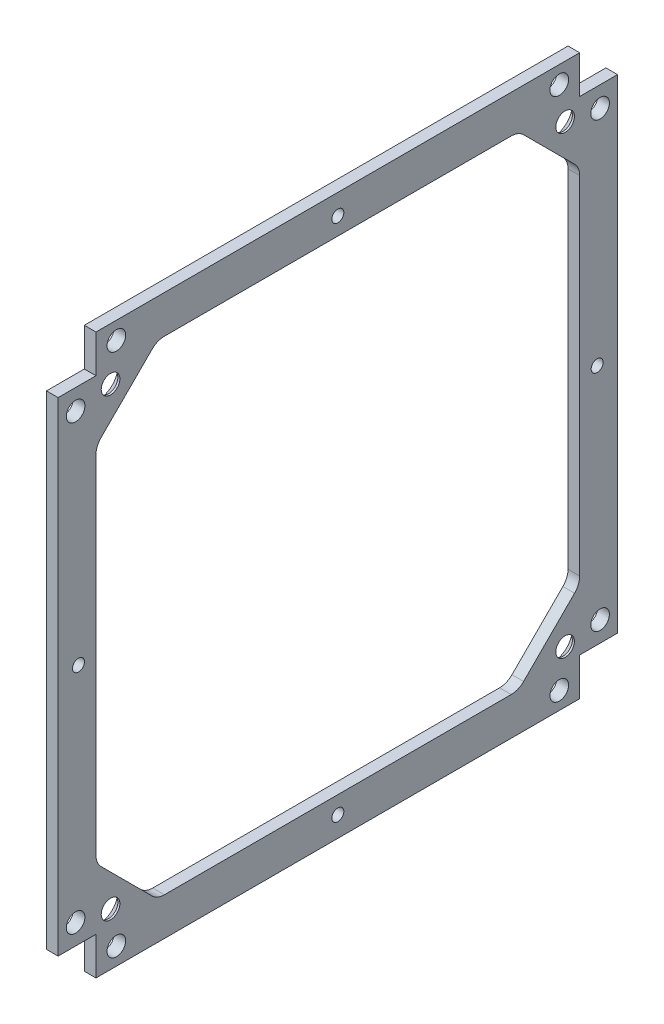
SolidWorks part; units mm, degrees
ref_plane "Front Plane" through (0, 0, 0) normal (0, 0, 1) x (1, 0, 0)
ref_plane "Top Plane" through (0, 0, 0) normal (0, 1, 0) x (1, 0, 0)
ref_plane "Right Plane" through (0, 0, 0) normal (1, 0, 0) x (0, 0, -1)
sketch "Sketch2" plane through (-51.4936, 0, 0) normal (-1, 0, 0) x (0, 0, 1)
  line L0 (0.9347, 3.4519) -> (7.4347, 3.4519)
  line L1 (7.4347, 3.4519) -> (7.4347, 86.4519)
  line L2 (0.9347, 92.9519) -> (-82.0653, 92.9519)
  line L3 (-88.5653, 86.4519) -> (-88.5653, 3.4519)
  line L4 (-82.0653, -3.0481) -> (0.9347, -3.0481)
  line L5 (0.9347, -3.0481) -> (0.9347, 3.4519)
  line L6 (-82.0653, -3.0481) -> (-82.0653, 3.4519)
  line L7 (-82.0653, 3.4519) -> (-88.5653, 3.4519)
  line L8 (-71.5653, 86.4519) -> (-82.0653, 75.9519)
  line L9 (-82.0653, 75.9519) -> (-82.0653, 13.9519)
  line L10 (-82.0653, 13.9519) -> (-71.5653, 3.4519)
  line L11 (-88.5653, 86.4519) -> (-82.0653, 86.4519)
  line L12 (-82.0653, 92.9519) -> (-82.0653, 86.4519)
  line L13 (-71.5653, 3.4519) -> (-9.5653, 3.4519)
  line L14 (-9.5653, 3.4519) -> (0.9347, 13.9519)
  line L15 (7.4347, 86.4519) -> (0.9347, 86.4519)
  line L16 (0.9347, 92.9519) -> (0.9347, 86.4519)
  line L17 (0.9347, 13.9519) -> (0.9347, 75.9519)
  line L18 (0.9347, 75.9519) -> (-9.5653, 86.4519)
  line L19 (-9.5653, 86.4519) -> (-71.5653, 86.4519)
  dimension "D1" = 6.5
  dimension "D2" = 6.5
  dimension "D3" = 6.5
  dimension "D4" = 6.5
  dimension "D5" = 6.5
  dimension "D6" = 6.5
extrude "Boss-Extrude2" add sketch "Sketch2" along normal blind 2
hole_wizard "CSK for M3 Flat Countersunk Head Screw3" positions "Sketch11" profile "Sketch10" countersink size "M3" standard "JIS" end condition through all
sketch "Sketch11" plane through (-53.4936, 0, 0) normal (-1, 0, 0) x (0, 0, 1)
  line L0 (0.9347, 3.4519) -> (7.4347, 3.4519) construction
  line L1 (0.9347, -3.0481) -> (0.9347, 3.4519) construction
  point P0 (-1.5653, 5.9519)
  dimension "D1" = 2.5
  dimension "D2" = 2.5
sketch "Sketch10" plane through (-53.4936, 5.9519, -1.5653) normal (0, 1, 0) x (0, 0, 1)
  line L0 (0, 0) -> (0, 2)
  line L1 (0, 2) -> (1.6, 2)
  line L2 (1.6, 2) -> (1.6, 1.65)
  line L3 (1.6, 1.65) -> (3.25, 0)
  line L5 (3.25, 0) -> (0, 0)
  line L6 (-1.6, 1.65) -> (-3.25, 0) construction
  line L11 (0, -6.35) -> (0, 107.95) construction
  dimension "Thru Hole Dia." = 3.2
  dimension "Thru Hole Depth" = 2
  dimension "Near C'Sink Dia." = 6.5
  dimension "Near C'Sink Angle" = 90
hole_wizard "Ø3.2 (3.2) Diameter Hole1" positions "Sketch13" profile "Sketch12" hole size "Ø3.2" standard "Ansi Metric" end condition up to next
sketch "Sketch13" plane through (-53.4936, 0, 0) normal (-1, 0, 0) x (0, 0, 1)
  line L0 (0.9347, 3.4519) -> (7.4347, 3.4519) construction
  line L1 (7.4347, 3.4519) -> (7.4347, 86.4519) construction
  point P0 (4.4347, 6.9519)
  dimension "D1" = 3.5
  dimension "D2" = 3
sketch "Sketch12" plane through (-53.4936, 6.9519, 4.4347) normal (0, 1, 0) x (0, 0, 1)
  line L0 (0, 0) -> (0, 2)
  line L1 (0, 2) -> (1.6, 2)
  line L2 (1.6, 2) -> (1.6, 0)
  line L5 (1.6, 0) -> (0, 0)
  line L11 (0, -6.35) -> (0, 107.95) construction
  dimension "Thru Hole Dia." = 3.2
  dimension "Thru Hole Depth" = 2
hole_wizard "Ø3.2 (3.2) Diameter Hole2" positions "Sketch15" profile "Sketch14" hole size "Ø3.2" standard "Ansi Metric" end condition up to next
sketch "Sketch15" plane through (-53.4936, 0, 0) normal (-1, 0, 0) x (0, 0, 1)
  line L0 (0.9347, -3.0481) -> (0.9347, 3.4519) construction
  line L1 (-82.0653, -3.0481) -> (0.9347, -3.0481) construction
  point P0 (-2.5653, -0.0481)
  dimension "D1" = 3.5
  dimension "D2" = 3
sketch "Sketch14" plane through (-53.4936, -0.0481, -2.5653) normal (0, 1, 0) x (0, 0, 1)
  line L0 (0, 0) -> (0, 2)
  line L1 (0, 2) -> (1.6, 2)
  line L2 (1.6, 2) -> (1.6, 0)
  line L5 (1.6, 0) -> (0, 0)
  line L11 (0, -6.35) -> (0, 107.95) construction
  dimension "Thru Hole Dia." = 3.2
  dimension "Thru Hole Depth" = 2
hole_wizard "Ø3.2 (3.2) Diameter Hole3" positions "Sketch19" profile "Sketch18" hole size "Ø3.2" standard "Ansi Metric" end condition up to next
sketch "Sketch19" plane through (-53.4936, 0, 0) normal (-1, 0, 0) x (0, 0, 1)
  line L0 (-82.0653, 3.4519) -> (-82.0653, -3.0481) construction
  line L1 (-82.0653, -3.0481) -> (0.9347, -3.0481) construction
  point P0 (-78.5653, -0.0481)
  dimension "D1" = 3.5
  dimension "D2" = 3
sketch "Sketch18" plane through (-53.4936, -0.0481, -78.5653) normal (0, 1, 0) x (0, 0, 1)
  line L0 (0, 0) -> (0, 2)
  line L1 (0, 2) -> (1.6, 2)
  line L2 (1.6, 2) -> (1.6, 0)
  line L5 (1.6, 0) -> (0, 0)
  line L11 (0, -6.35) -> (0, 107.95) construction
  dimension "Thru Hole Dia." = 3.2
  dimension "Thru Hole Depth" = 2
sketch "Sketch20" plane through (-53.4936, 0, 0) normal (-1, 0, 0) x (0, 0, 1)
  line L0 (-88.5653, 3.4519) -> (-82.0653, 3.4519) construction
  line L1 (-88.5653, 86.4519) -> (-88.5653, 3.4519) construction
  line L2 (-82.0653, 86.4519) -> (-88.5653, 86.4519) construction
  line L3 (-82.0653, 92.9519) -> (-82.0653, 86.4519) construction
  line L4 (0.9347, 92.9519) -> (-82.0653, 92.9519) construction
  line L5 (0.9347, 86.4519) -> (0.9347, 92.9519) construction
  line L6 (7.4347, 86.4519) -> (0.9347, 86.4519) construction
  line L7 (7.4347, 3.4519) -> (7.4347, 86.4519) construction
  point P0 (-85.5653, 6.9519)
  point P1 (-85.5653, 82.9519)
  point P2 (-78.5653, 89.9519)
  point P3 (-2.5653, 89.9519)
  point P4 (4.4347, 82.9519)
  dimension "D1" = 3.5
  dimension "D2" = 3
  dimension "D3" = 3
  dimension "D4" = 3.5
  dimension "D5" = 3.5
  dimension "D6" = 3
  dimension "D7" = 3
  dimension "D8" = 3.5
  dimension "D9" = 3.5
  dimension "D10" = 3
hole_wizard "Ø3.2 (3.2) Diameter Hole5" positions "3DSketch1" profile "Sketch23" hole size "Ø3.2" standard "Ansi Metric"
sketch3d "3DSketch1"
  point P0 (-53.4936, 6.9519, -85.5653)
  point P3 (-53.4936, 82.9519, -85.5653)
  point P6 (-53.4936, 89.9519, -78.5653)
  point P9 (-53.4936, 89.9519, -2.5653)
  point P12 (-53.4936, 82.9519, 4.4347)
sketch "Sketch23" plane through (-53.4936, 6.9519, -85.5653) normal (0, 1, 0) x (0, 0, 1)
  line L0 (0, 0) -> (0, 10.9614)
  line L1 (0, 10.9614) -> (1.6, 10)
  line L2 (1.6, 10) -> (1.6, 0)
  line L5 (1.6, 0) -> (0, 0)
  line L10 (0, 10.9614) -> (-1.6, 10) construction
  line L11 (0, -6.35) -> (0, 107.95) construction
  dimension "Hole Dia." = 3.2
  dimension "Hole Depth" = 10
  dimension "Drill Angle" = 118
hole_wizard "CSK for M3 Flat Countersunk Head Screw5" positions "3DSketch2" profile "Sketch24" countersink size "M3" standard "JIS" end condition up to next
sketch3d "3DSketch2"
  line L0 (-53.4936, 3.4519, -82.0653) -> (-53.4936, -3.0481, -82.0653) construction
  line L1 (-53.4936, 3.4519, -88.5653) -> (-53.4936, 3.4519, -82.0653) construction
  line L2 (-53.4936, 92.9519, -82.0653) -> (-53.4936, 86.4519, -82.0653) construction
  line L3 (-53.4936, 86.4519, -82.0653) -> (-53.4936, 86.4519, -88.5653) construction
  line L4 (-53.4936, 86.4519, 0.9347) -> (-53.4936, 92.9519, 0.9347) construction
  line L5 (-53.4936, 86.4519, 7.4347) -> (-53.4936, 86.4519, 0.9347) construction
  point P0 (-53.4936, 5.9519, -79.5653)
  point P2 (-53.4936, 83.9519, -79.5653)
  point P4 (-53.4936, 83.9519, -1.5653)
  dimension "D1" = 2.5
  dimension "D2" = 2.5
  dimension "D3" = 2.5
  dimension "D4" = 2.5
  dimension "D5" = 2.5
  dimension "D6" = 2.5
sketch "Sketch24" plane through (-53.4936, 5.9519, -79.5653) normal (0, 1, 0) x (0, 0, 1)
  line L0 (0, 0) -> (0, 2)
  line L1 (0, 2) -> (1.6, 2)
  line L2 (1.6, 2) -> (1.6, 1.65)
  line L3 (1.6, 1.65) -> (3.25, 0)
  line L5 (3.25, 0) -> (0, 0)
  line L6 (-1.6, 1.65) -> (-3.25, 0) construction
  line L11 (0, -6.35) -> (0, 107.95) construction
  dimension "Thru Hole Dia." = 3.2
  dimension "Thru Hole Depth" = 2
  dimension "Near C'Sink Dia." = 6.5
  dimension "Near C'Sink Angle" = 90
fillet "Fillet1" radius 3 8 edges at (-52.4936, 13.9519, -82.0653) (-52.4936, 3.4519, -71.5653) (-52.4936, 3.4519, -9.5653) (-52.4936, 13.9519, 0.9347) (-52.4936, 75.9519, 0.9347) (-52.4936, 86.4519, -9.5653) (-52.4936, 86.4519, -71.5653) (-52.4936, 75.9519, -82.0653)
hole_wizard "M2.5x0.45 Tapped Hole1" positions "3DSketch3" profile "Sketch25" tap size "M2.5x0.45" standard "Ansi Metric" end condition up to next
sketch3d "3DSketch3"
  line L0 (-53.4936, 92.9519, 0.9347) -> (-53.4936, 92.9519, -82.0653) construction
  line L1 (-53.4936, 86.4519, 0.9347) -> (-53.4936, 92.9519, 0.9347) construction
  line L2 (-53.4936, 86.4519, 7.4347) -> (-53.4936, 86.4519, 0.9347) construction
  line L3 (-53.4936, 3.4519, 7.4347) -> (-53.4936, 86.4519, 7.4347) construction
  line L4 (-53.4936, -3.0481, -82.0653) -> (-53.4936, -3.0481, 0.9347) construction
  line L5 (-53.4936, -3.0481, 0.9347) -> (-53.4936, 3.4519, 0.9347) construction
  line L6 (-53.4936, 86.4519, -88.5653) -> (-53.4936, 3.4519, -88.5653) construction
  line L7 (-53.4936, 3.4519, -88.5653) -> (-53.4936, 3.4519, -82.0653) construction
  point P0 (-53.4936, 89.4519, -40.5653)
  point P2 (-53.4936, 44.9519, -85.0653)
  point P4 (-53.4936, 0.4519, -40.5653)
  point P6 (-53.4936, 44.9519, 3.9347)
  dimension "D1" = 3.5
  dimension "D2" = 41.5
  dimension "D3" = 41.5
  dimension "D4" = 3.5
  dimension "D5" = 3.5
  dimension "D6" = 41.5
  dimension "D7" = 3.5
  dimension "D8" = 41.5
sketch "Sketch25" plane through (-53.4936, 89.4519, -40.5653) normal (0, 1, 0) x (0, 0, 1)
  line L0 (0, 0) -> (0, 2)
  line L1 (0, 2) -> (1.025, 2)
  line L2 (1.025, 2) -> (1.025, 0)
  line L5 (1.025, 0) -> (0, 0)
  line L11 (0, -6.35) -> (0, 107.95) construction
  dimension "Thru Tap Drill Dia." = 2.05
  dimension "Thru Tap Drill Depth" = 2
cosmetic thread "Hole Thread1"
cosmetic thread "Hole Thread2"
cosmetic thread "Hole Thread3"
cosmetic thread "Hole Thread4"
